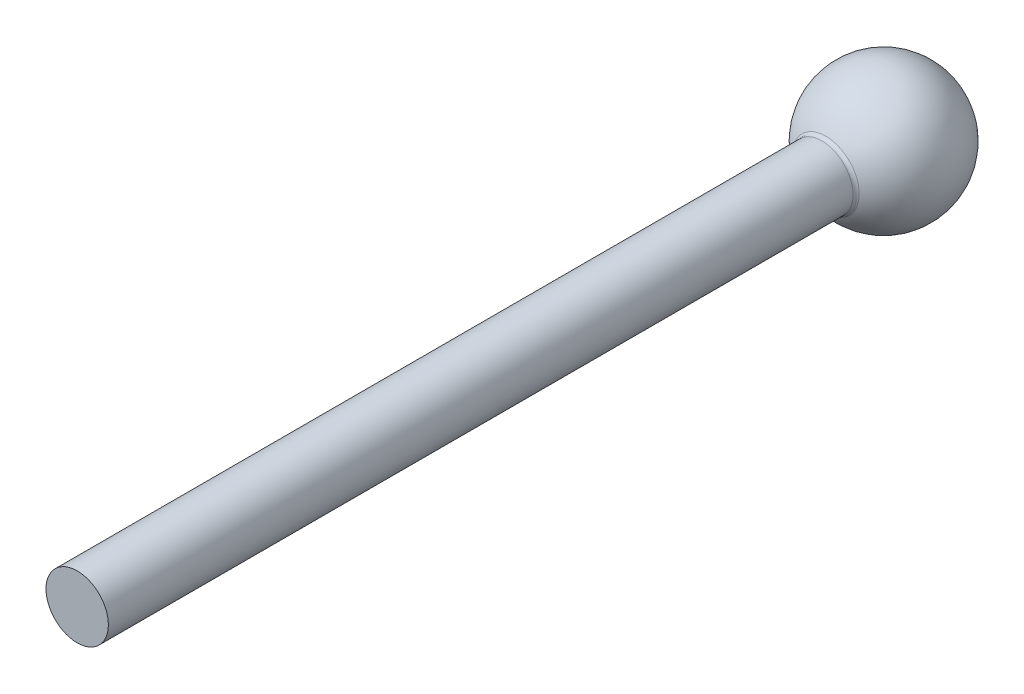
SolidWorks part; units mm, degrees
material "AISI 1045 Aço, trefilado"
ref_plane "Plano frontal" through (0, 0, 0) normal (0, 0, 1) x (1, 0, 0)
ref_plane "Plano superior" through (0, 0, 0) normal (0, 1, 0) x (1, 0, 0)
ref_plane "Plano direito" through (0, 0, 0) normal (1, 0, 0) x (0, 0, -1)
sketch "Esboço1" plane through (0, 0, 0) normal (0, 0, 1) x (1, 0, 0)
  circle A0 centre (0, 0) radius 3.5
  dimension "D1" = 7
extrude "Ressalto-extrusão1" add sketch "Esboço1" along normal blind 85
cosmetic thread "Representação de rosca1" parameters "D1"=32, "D2"=4.891
sketch "Esboço2" plane through (0, 0, 0) normal (0, 1, 0) x (1, 0, 0)
  line L0 (0, 13) -> (0, -85) construction
  line L2 (-3.5, -85) -> (3.5, -85) construction
  line L3 (0, 13) -> (0, -2)
  arc A0 (0, 13) -> (0, -2) centre (0, 5.5) ccw
  dimension "D1" = 15
  dimension "D2" = 98
revolve "Revolução7" add sketch "Esboço2" angle 360 about L0
fillet "Filete1" radius 0.5 1 edges at (-3.5, 0, 1.1332)
